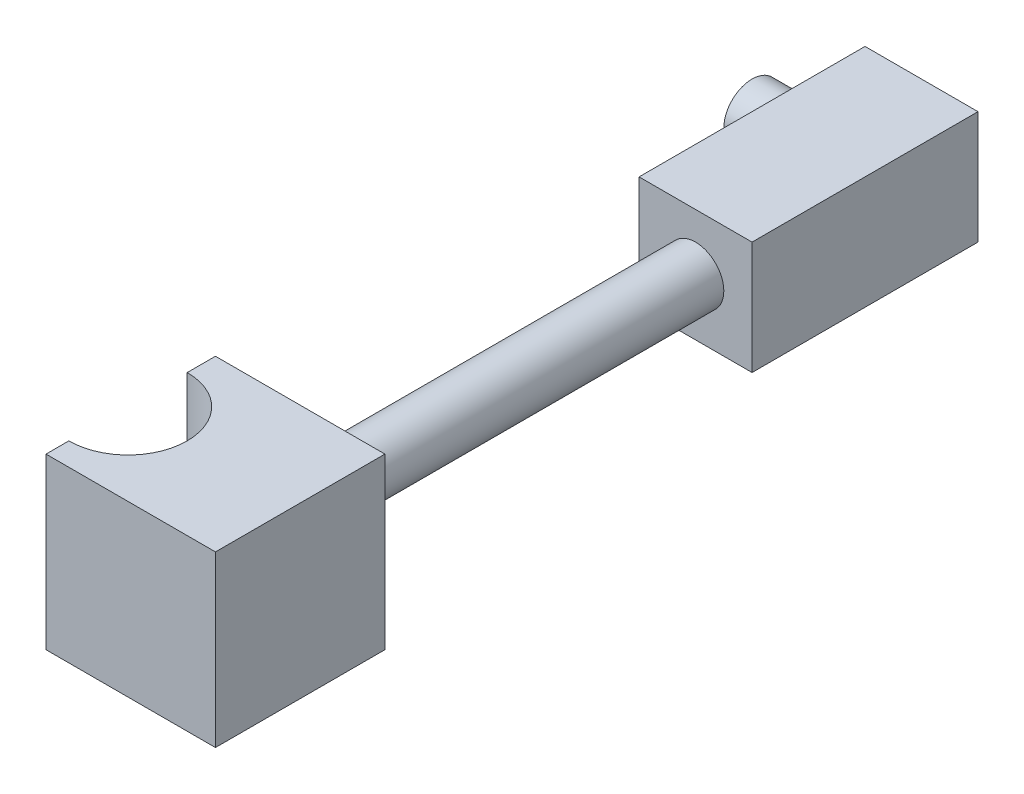
SolidWorks part; units mm, degrees
ref_plane "Front Plane" through (0, 0, 0) normal (0, 0, 1) x (1, 0, 0)
ref_plane "Top Plane" through (0, 0, 0) normal (0, 1, 0) x (1, 0, 0)
ref_plane "Right Plane" through (0, 0, 0) normal (1, 0, 0) x (0, 0, -1)
sketch "Sketch1" plane through (0, 0, 0) normal (0, 1, 0) x (1, 0, 0)
  line L1 (-6.4835, 21.9231) -> (13.5165, 21.9231)
  line L2 (-6.4835, 21.9231) -> (-6.4835, -18.0769)
  line L3 (-6.4835, -18.0769) -> (13.5165, -18.0769)
  line L4 (13.5165, 21.9231) -> (13.5165, -18.0769)
  dimension "D1" = 20
  dimension "D2" = 40
extrude "Boss-Extrude1" add sketch "Sketch1" along normal blind 20
sketch "Sketch2" plane through (-6.4835, 0, 0) normal (-1, 0, 0) x (0, 0, 1)
  line L0 (-21.9231, 20) -> (-21.9231, 0) construction
  line L1 (-21.9231, 20) -> (18.0769, 20) construction
  circle A0 centre (-11.9231, 10) radius 5
  dimension "D1" = 10
  dimension "D2" = 10
extrude "Boss-Extrude2" add sketch "Sketch2" along normal blind 10 contours A0
sketch "Sketch3" plane through (0, 0, 18.0769) normal (0, 0, 1) x (1, 0, 0)
  line L0 (-6.4835, 20) -> (13.5165, 20) construction
  line L1 (13.5165, 20) -> (13.5165, 0) construction
  circle A0 centre (3.5165, 10) radius 5
  dimension "D1" = 10
  dimension "D2" = 10
extrude "Boss-Extrude3" add sketch "Sketch3" along normal blind 70 contours A0
sketch "Sketch4" plane through (0, 0, 88.0769) normal (0, 0, 1) x (1, 0, 0)
  line L0 (13.5165, 20) -> (13.5165, 0) construction
  line L1 (-11.4835, 25) -> (18.5165, 25)
  line L2 (-11.4835, 25) -> (-11.4835, -5)
  line L3 (-11.4835, -5) -> (18.5165, -5)
  line L4 (18.5165, 25) -> (18.5165, -5)
  line L5 (-6.4835, 0) -> (13.5165, 0) construction
  dimension "D1" = 30
  dimension "D2" = 30
  dimension "D3" = 5
  dimension "D4" = 5
extrude "Boss-Extrude4" add sketch "Sketch4" along normal blind 30
sketch "Sketch7" plane through (0, 25, 0) normal (0, 1, 0) x (1, 0, 0)
  line L0 (-11.4835, -93.0769) -> (-11.4835, -114.0358)
  line L1 (-11.4835, -118.0769) -> (-11.4835, -88.0769) construction
  line L2 (18.5165, -88.0769) -> (-11.4835, -88.0769) construction
  arc A0 (-11.4835, -93.0769) -> (-11.4835, -114.0358) centre (-11.4835, -103.5564) cw
  line M2 (-11.4835, -88.0769) -> (-11.4835, -118.0769)
  dimension "D1" = 5
extrude "Cut-Extrude1" cut sketch "Sketch7" against normal blind 30 contours A0 M2
ref_plane "Plane1" through (-56.4835, 0, 0) normal (-1, 0, 0) x (0, 0, 1)
